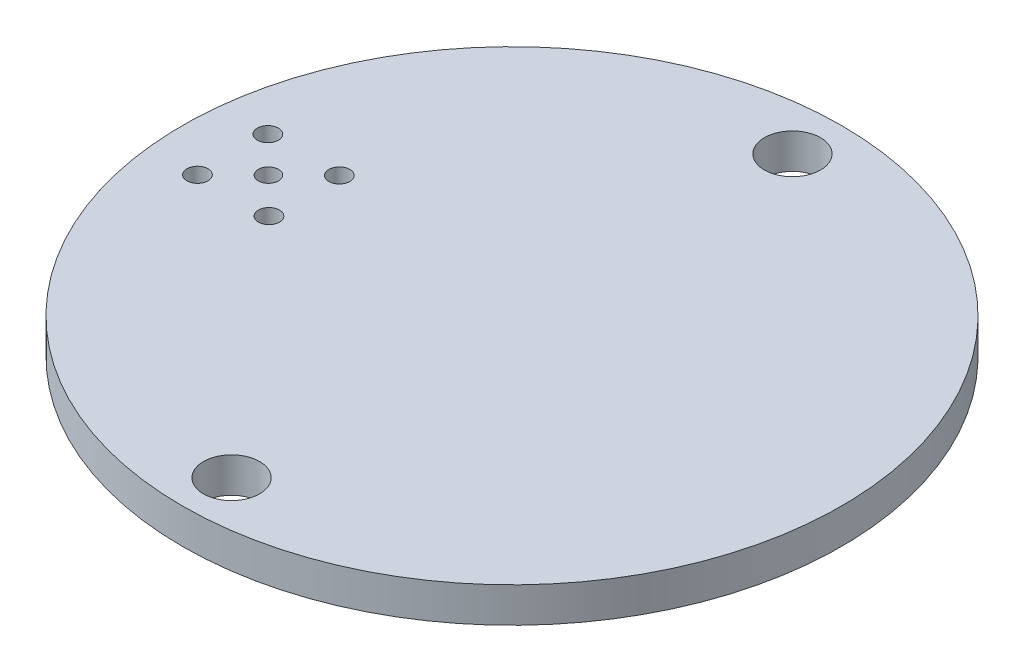
SolidWorks part; units mm, degrees
ref_plane "Plano frontal" through (0, 0, 0) normal (0, 0, 1) x (1, 0, 0)
ref_plane "Plano superior" through (0, 0, 0) normal (0, 1, 0) x (1, 0, 0)
ref_plane "Plano direito" through (0, 0, 0) normal (1, 0, 0) x (0, 0, -1)
sketch "Esboço1" plane through (0, 0, 0) normal (0, 1, 0) x (1, 0, 0)
  line L0 (-32.2938, 0) -> (31.3438, 0) construction
  line L1 (0, 28.557) -> (0, -26.2938) construction
  circle A0 centre (0, 0) radius 23.5
  circle A1 centre (0, -20) radius 2
  circle A2 centre (0, 20) radius 2
  circle A3 centre (-19.9202, 2.51) radius 0.75
  circle A4 centre (-14.8202, 2.51) radius 0.75
  circle A5 centre (-14.8202, -2.51) radius 0.75
  circle A6 centre (-19.9202, -2.51) radius 0.75
  circle A7 centre (-17.3702, 0) radius 0.7188
  point P15 (0, 0)
  dimension "D1" = 47
  dimension "D2" = 20
  dimension "D3" = 1.5
  dimension "D4" = 1.5
  dimension "D5" = 5.1
  dimension "D6" = 2.51
  dimension "D7" = 2.55
extrude "Ressalto-extrusão1" add sketch "Esboço1" along normal blind 2.5
